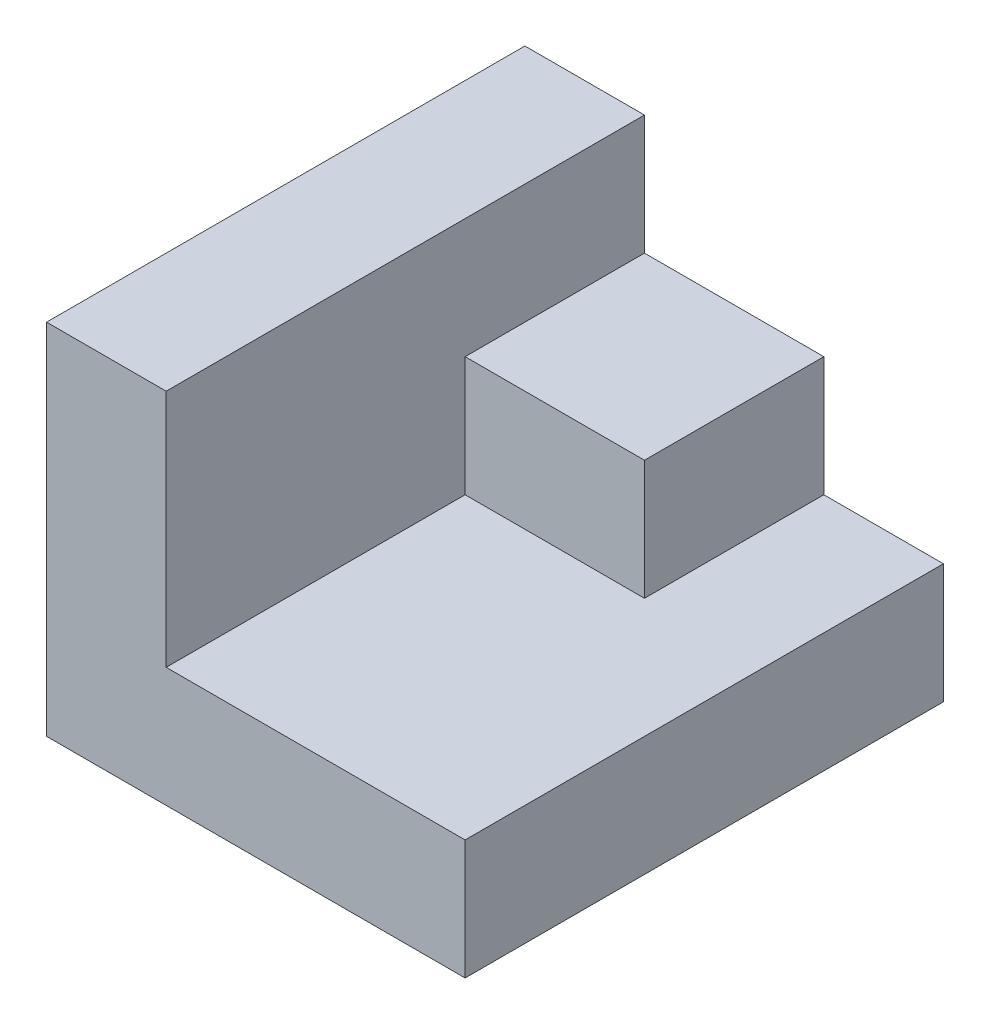
SolidWorks part; units mm, degrees
ref_plane "Front Plane" through (0, 0, 0) normal (0, 0, 1) x (1, 0, 0)
ref_plane "Top Plane" through (0, 0, 0) normal (0, 1, 0) x (1, 0, 0)
ref_plane "Right Plane" through (0, 0, 0) normal (1, 0, 0) x (0, 0, -1)
sketch "Sketch1" plane through (0, 0, 0) normal (0, 0, 1) x (1, 0, 0)
  line L0 (0, 30) -> (0, 0)
  line L1 (0, 0) -> (35, 0)
  line L2 (35, 0) -> (35, 10)
  line L3 (35, 10) -> (10, 10)
  line L4 (10, 10) -> (10, 30)
  line L5 (10, 30) -> (0, 30)
  dimension "D1" = 35
  dimension "D2" = 30
  dimension "D3" = 10
  dimension "D4" = 20
  dimension "D5" = 10
  dimension "D6" = 25
extrude "Boss-Extrude1" add sketch "Sketch1" against normal blind 40
sketch "Sketch2" plane through (0, 0, -40) normal (0, 0, -1) x (-1, 0, 0)
  line L1 (-10, 10) -> (-25, 10)
  line L2 (-10, 10) -> (-10, 20)
  line L3 (-10, 20) -> (-25, 20)
  line L4 (-25, 10) -> (-25, 20)
  dimension "D1" = 15
  dimension "D2" = 10
extrude "Boss-Extrude2" add sketch "Sketch2" against normal blind 15
